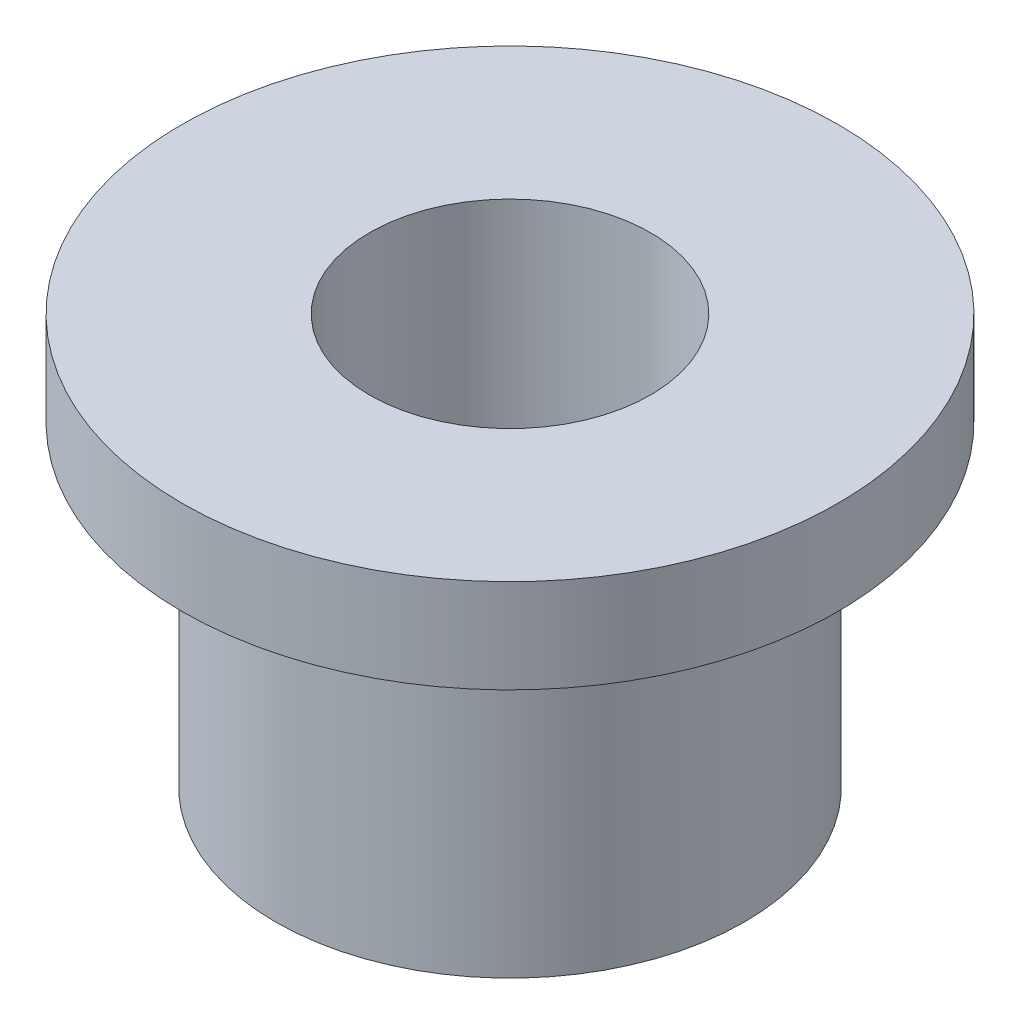
SolidWorks part; units mm, degrees
ref_plane "Front Plane" through (0, 0, 0) normal (0, 0, 1) x (1, 0, 0)
ref_plane "Top Plane" through (0, 0, 0) normal (0, 1, 0) x (1, 0, 0)
ref_plane "Right Plane" through (0, 0, 0) normal (1, 0, 0) x (0, 0, -1)
sketch "Sketch1" plane through (0, 0, 0) normal (0, 1, 0) x (1, 0, 0)
  circle A0 centre (0, 0) radius 7.9375
  circle A1 centre (0, 0) radius 4.7625
extrude "Boss-Extrude1" add sketch "Sketch1" along normal blind 10.7
sketch "Sketch2" plane through (0, 10.7, 0) normal (0, 1, 0) x (1, 0, 0)
  circle A0 centre (0, 0) radius 4.7625
  circle A1 centre (0, 0) radius 11.1125
extrude "Boss-Extrude2" add sketch "Sketch2" along normal blind 3.175
